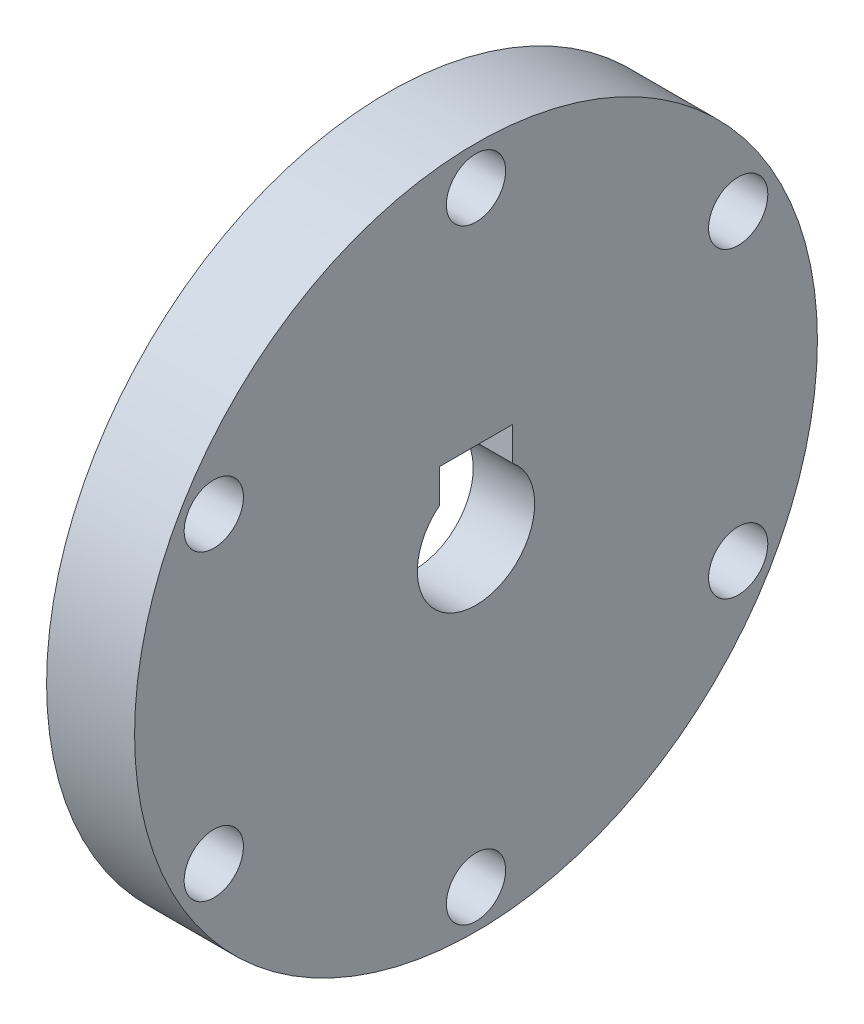
SolidWorks part; units mm, degrees
material "6061-T6 (SS)"
ref_plane "Front Plane" through (0, 0, 0) normal (0, 0, 1) x (1, 0, 0)
ref_plane "Top Plane" through (0, 0, 0) normal (0, 1, 0) x (1, 0, 0)
ref_plane "Right Plane" through (0, 0, 0) normal (1, 0, 0) x (0, 0, -1)
sketch "Sketch1" plane through (0, 0, 0) normal (1, 0, 0) x (0, 0, -1)
  line L0 (0, 0) -> (0, 20.64) construction
  arc A0 (-1.6237, 23.2194) -> (1.6237, -23.2194) centre (0, 0) ccw construction
  arc A1 (1.0588, 18.9205) -> (-1.0588, 22.3595) centre (0, 20.64) ccw construction
  circle A2 centre (0, 0) radius 23.2761
  circle A3 centre (0, 20.64) radius 2.0193
  circle A4 centre (17.8748, 10.32) radius 2.0193
  circle A5 centre (17.8748, -10.32) radius 2.0193
  circle A6 centre (0, -20.64) radius 2.0193
  circle A7 centre (-17.8748, -10.32) radius 2.0193
  circle A8 centre (-17.8748, 10.32) radius 2.0193
  circle A9 centre (0, 0) radius 17.46 construction
  point P21 (0, 0)
  dimension "D1" = 23.2761
  dimension "D2" = 2.0193
  dimension "D3" = 20.64
  dimension "D5" = 34.92
  dimension "D4" = 6
extrude "Boss-Extrude1" add sketch "Sketch1" along normal blind 6
sketch "Sketch2" plane through (0, 0, 0) normal (-1, 0, 0) x (0, 0, 1)
  circle A0 centre (0, 0) radius 17.46 construction
  circle A1 centre (0, 0) radius 17.46
  circle A2 centre (0, 0) radius 15
  dimension "D1" = 30
extrude "Boss-Extrude2" add sketch "Sketch2" along normal blind 2
chamfer "Chamfer1" [suppressed] distance 1 angle 45
sketch "Sketch3" plane through (0, 0, 0) normal (-1, 0, 0) x (0, 0, 1)
  circle A0 centre (0, 0) radius 4
  dimension "D1" = 8
sketch "Sketch4" plane through (0, 0, 0) normal (-1, 0, 0) x (0, 0, 1)
  circle A0 centre (0, 0) radius 15 construction
  circle A1 centre (0, 0) radius 15
extrude "Cut-Extrude2" cut sketch "Sketch4" against normal blind 1.8125
sketch "Sketch5" plane through (6, 0, 0) normal (1, 0, 0) x (0, 0, -1)
  circle A0 centre (0, 0) radius 7.5
  circle A1 centre (0, 0) radius 15
  circle A2 centre (0, 0) radius 17.5
  dimension "D1" = 15
  dimension "D2" = 30
  dimension "D3" = 35
chamfer "Chamfer4" distance 2.5 angle 45 1 edges at (1.8125, 0, 15)
chamfer "Chamfer5" distance 1 angle 45 1 edges at (-2, 0, 17.46)
sketch "Sketch6" plane through (6, 0, 0) normal (1, 0, 0) x (0, 0, -1)
  circle A2 centre (0, 0) radius 12
  dimension "D1" = 24
sketch "Sketch7" plane through (6, 0, 0) normal (1, 0, 0) x (0, 0, -1)
  line L0 (0, 0) -> (0, 3.0697) construction
  line L3 (-2.5, 3.1225) -> (-2.5, 5.4225)
  line L4 (-2.5, 5.4225) -> (2.5, 5.4225)
  line L5 (2.5, 3.1225) -> (2.5, 5.4225)
  line L6 (-2.1328, 1.0624) -> (2.5, 5.4225) construction
  line L7 (-2.5, 5.4225) -> (2.1328, 1.0624) construction
  arc A0 (-2.5, 3.1225) -> (2.5, 3.1225) centre (0, 0) ccw
  dimension "D1" = 8
  dimension "D2" = 5
  dimension "D3" = 2.3
extrude "Cut-Extrude3" cut sketch "Sketch7" against normal blind 20.5
